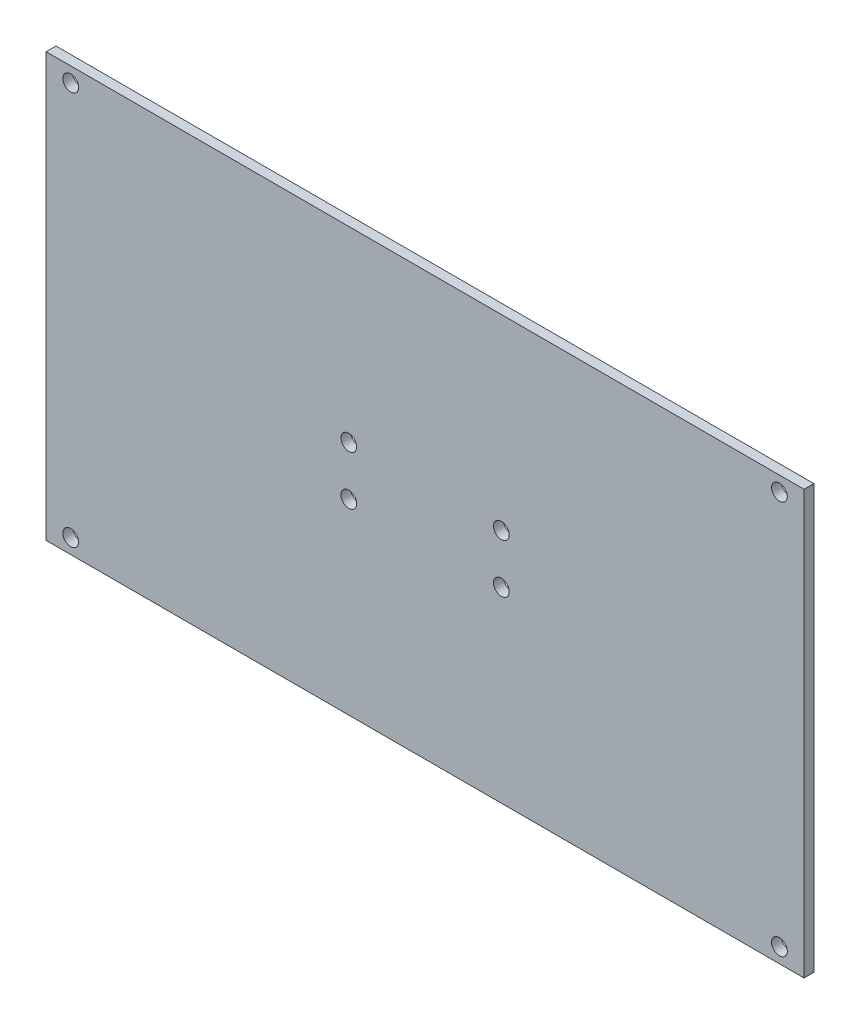
SolidWorks part; units mm, degrees
ref_plane "前视基准面" through (0, 0, 0) normal (0, 0, 1) x (1, 0, 0)
ref_plane "上视基准面" through (0, 0, 0) normal (0, 1, 0) x (1, 0, 0)
ref_plane "右视基准面" through (0, 0, 0) normal (1, 0, 0) x (0, 0, -1)
sketch "草图1" plane through (0, 0, 0) normal (0, 0, 1) x (1, 0, 0)
  line L0 (-160, 43) -> (-6, 43) construction
  line L1 (-160, 86) -> (-6, 86)
  line L2 (-160, 86) -> (-160, 0)
  line L3 (-160, 0) -> (-6, 0)
  line L4 (-6, 86) -> (-6, 0)
  line L5 (-15, 0) -> (0, 0) construction
  circle A0 centre (-155, 3) radius 1.6
  circle A1 centre (-11, 83) radius 1.6 construction
  circle A3 centre (-11, 3) radius 1.6 construction
  circle A5 centre (-11, 3) radius 1.6
  circle A6 centre (-11, 83) radius 1.6
  circle A7 centre (-155, 83) radius 1.6
  dimension "D2" = 5
  dimension "D4" = 3.2
  dimension "D5" = 144
  dimension "D6" = 3
  dimension "D1" = 5
  dimension "D3" = 86
extrude "凸台-拉伸1" add sketch "草图1" along normal blind 2
sketch "草图2" plane through (0, 0, 2) normal (0, 0, 1) x (1, 0, 0)
  line L0 (-83, 86) -> (-83, 0) construction
  line L1 (-6, 86) -> (-160, 86) construction
  line L2 (-160, 0) -> (-6, 0) construction
  line L3 (-160, 43) -> (-6, 43) construction
  line L4 (-160, 86) -> (-160, 0) construction
  line L5 (-6, 0) -> (-6, 86) construction
  circle A0 centre (-98.5, 48) radius 1.6
  circle A1 centre (-67.5, 48) radius 1.6
  circle A2 centre (-67.5, 38) radius 1.6
  circle A3 centre (-98.5, 38) radius 1.6
  dimension "D1" = 3.2
  dimension "D2" = 31
  dimension "D3" = 10
extrude "切除-拉伸1" cut sketch "草图2" against normal up to next
